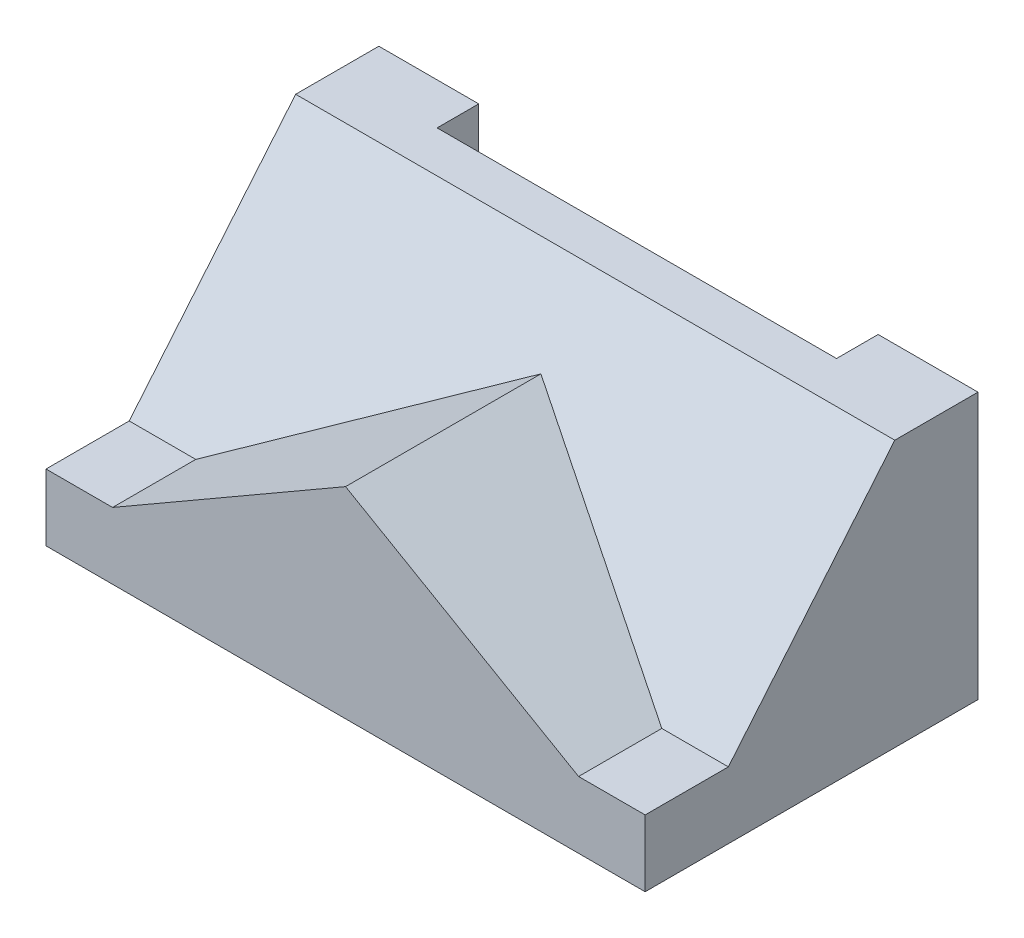
SolidWorks part; units mm, degrees
ref_plane "Front Plane" through (0, 0, 0) normal (0, 0, 1) x (1, 0, 0)
ref_plane "Top Plane" through (0, 0, 0) normal (0, 1, 0) x (1, 0, 0)
ref_plane "Right Plane" through (0, 0, 0) normal (1, 0, 0) x (0, 0, -1)
sketch "Sketch1" plane through (0, 0, 0) normal (1, 0, 0) x (0, 0, -1)
  line L0 (-31.75, 0) -> (31.75, 0)
  line L1 (31.75, 0) -> (31.75, 50.8)
  line L2 (31.75, 50.8) -> (15.875, 50.8)
  line L3 (15.875, 50.8) -> (-15.875, 12.7)
  line L4 (-15.875, 12.7) -> (-31.75, 12.7)
  line L5 (-31.75, 12.7) -> (-31.75, 0)
  point P4 (0, 0)
  dimension "D1" = 63.5
  dimension "D2" = 50.8
  dimension "D3" = 15.875
  dimension "D4" = 12.7
  dimension "D5" = 15.875
extrude "Boss-Extrude1" add sketch "Sketch1" against normal blind 114.3
sketch "Sketch2" plane through (0, 50.8, 0) normal (0, 1, 0) x (1, 0, 0)
  line L0 (-57.15, 31.75) -> (-57.15, 15.875) construction
  line L1 (-114.3, 31.75) -> (0, 31.75) construction
  line L2 (-114.3, 15.875) -> (0, 15.875) construction
  line L3 (-114.3, 31.75) -> (-95.25, 31.75)
  line L4 (-95.25, 31.75) -> (-95.25, 23.8125)
  line L5 (-95.25, 23.8125) -> (-19.05, 23.8125)
  line L6 (-19.05, 23.8125) -> (-19.05, 31.75)
  line L7 (-19.05, 31.75) -> (0, 31.75)
  point P8 (-95.25, 23.8125)
  point P13 (-95.25, 31.75)
  line M2 (0, 31.75) -> (-114.3, 31.75)
  dimension "D1" = 19.05
  dimension "D2" = 7.9375
  dimension "D3" = 76.2
sketch "Sketch9" plane through (0, 50.8, 0) normal (0, 1, 0) x (1, 0, 0)
  line L0 (-78.2073, 24.636) -> (-78.2073, 23.8125)
  line L1 (-95.25, 23.8125) -> (-19.05, 23.8125) construction
extrude "Cut-Extrude1" cut sketch "Sketch2" against normal through all and the other way through all contours L0 L4 L5 M2 | L0 L5 L6 M2
sketch "Sketch10" plane through (0, 0, 31.75) normal (0, 0, 1) x (1, 0, 0)
  line L0 (-101.6, 12.7) -> (-12.7, 12.7)
  line L1 (-114.3, 12.7) -> (0, 12.7) construction
  line L2 (-57.15, 12.7) -> (-57.15, 64.0264) construction
  line L3 (-101.6, 12.7) -> (-57.15, 38.3632)
  line L4 (-57.15, 38.3632) -> (-12.7, 12.7)
  line L6 (-101.6, 12.7) -> (-114.3, 12.7)
  line L7 (-12.7, 12.7) -> (0, 12.7)
  point P5 (-57.15, 12.7)
  point P8 (-57.15, 12.7)
  line M7 (0, 12.7) -> (-114.3, 12.7)
  dimension "D1" = 12.7
  dimension "D2" = 12.7
  dimension "D3" = 120
extrude "Boss-Extrude2" add sketch "Sketch10" against normal up to surface (15.875 mm away) contours L0 L2 L3 | L2 L4 M7
